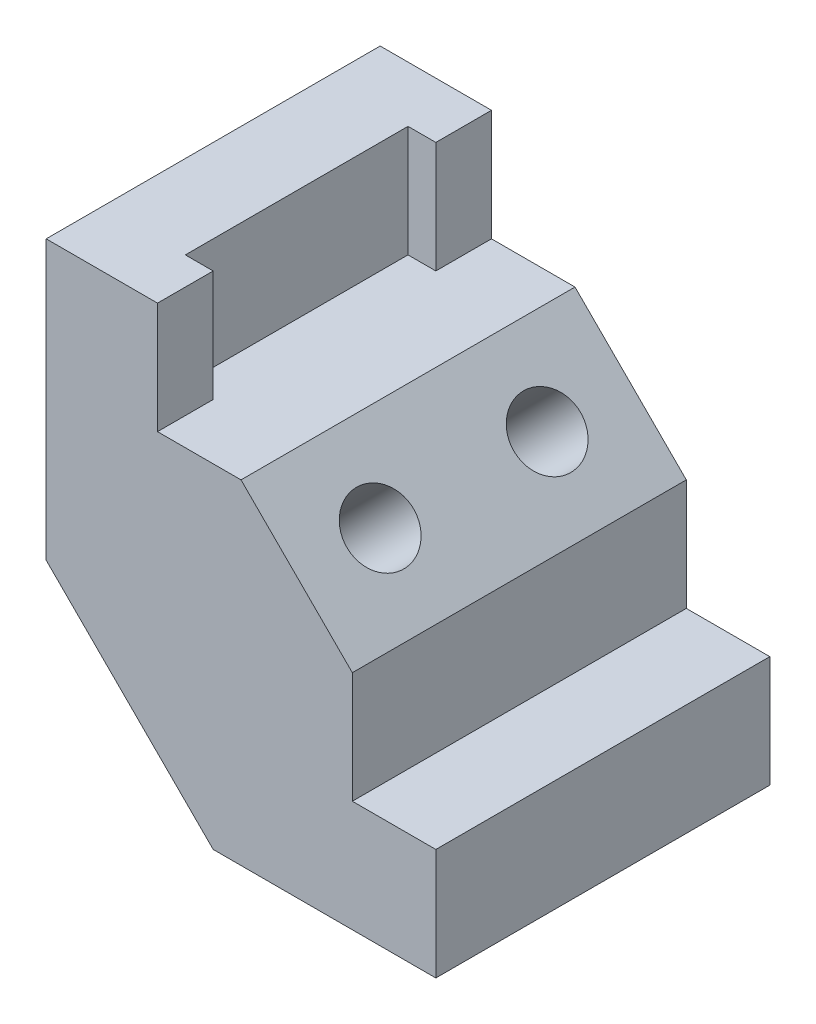
SolidWorks part; units mm, degrees
ref_plane "Front Plane" through (0, 0, 0) normal (0, 0, 1) x (1, 0, 0)
ref_plane "Top Plane" through (0, 0, 0) normal (0, 1, 0) x (1, 0, 0)
ref_plane "Right Plane" through (0, 0, 0) normal (1, 0, 0) x (0, 0, -1)
sketch "Sketch3" plane through (0, 0, 0) normal (0, 0, 1) x (1, 0, 0)
  line L0 (0, 18.3963) -> (0, -45.1037)
  line L1 (0, -45.1037) -> (38.1, -83.2037)
  line L2 (38.1, -83.2037) -> (88.9, -83.2037)
  line L3 (88.9, -83.2037) -> (88.9, -57.8037)
  line L4 (88.9, -57.8037) -> (69.85, -57.8037)
  line L5 (69.85, -57.8037) -> (69.85, -32.4037)
  line L6 (69.85, -32.4037) -> (44.45, -7.0037)
  line L7 (44.45, -7.0037) -> (25.4, -7.0037)
  line L8 (25.4, -7.0037) -> (25.4, 18.3963)
  line L9 (25.4, 18.3963) -> (0, 18.3963)
  point P11 (0, 0)
  dimension "D1" = 101.6
  dimension "D2" = 88.9
  dimension "D3" = 38.1
  dimension "D4" = 25.4
  dimension "D5" = 25.4
  dimension "D6" = 44.45
  dimension "D7" = 50.8
  dimension "D8" = 76.2
  dimension "D9" = 45
extrude "Boss-Extrude2" add sketch "Sketch3" along normal mid plane 76.2
sketch "Sketch7" plane through (0, 18.3963, 0) normal (0, 1, 0) x (1, 0, 0)
  line L2 (25.4, 25.4) -> (0, 25.4)
  line L3 (25.4, 25.4) -> (19.05, 25.4)
  line L5 (25.4, -25.4) -> (0, -25.4)
  line L6 (25.4, -25.4) -> (19.05, -25.4)
  line L7 (25.4, 25.4) -> (25.4, -25.4)
  line L8 (19.05, -38.1) -> (19.05, 38.1)
  line L9 (19.05, -25.4) -> (19.05, 25.4)
  dimension "D1" = 12.7
  dimension "D2" = 12.7
  dimension "D3" = 6.35
extrude "Cut-Extrude1" cut sketch "Sketch7" against normal up to surface (25.4 mm away) up to face at (34.925, -7.0037, 0)
sketch "Sketch8" plane through (18.7231, 18.7231, 0) normal (0.7071, 0.7071, 0) x (0, 0, -1)
  line L0 (-38.1, -72.3043) -> (38.1, -72.3043) construction
  line L1 (0, 13.0081) -> (0, -121.6957)
  line L2 (-38.1, 13.0081) -> (38.1, 13.0081) construction
  line L3 (-38.1, -121.6957) -> (38.1, -121.6957) construction
  line L4 (-19.05, -54.3465) -> (19.05, -54.3465)
  circle A0 centre (-19.05, -54.3465) radius 7.62
  circle A1 centre (19.05, -54.3465) radius 7.62
  dimension "D1" = 15.24
  dimension "D2" = 15.24
  dimension "D3" = 17.9578
  dimension "D4" = 17.9578
  dimension "D5" = 38.1
extrude "Cut-Extrude3" cut sketch "Sketch8" along direction (0.7071, 0.7071, 0) on the side against the normal blind 53.34
